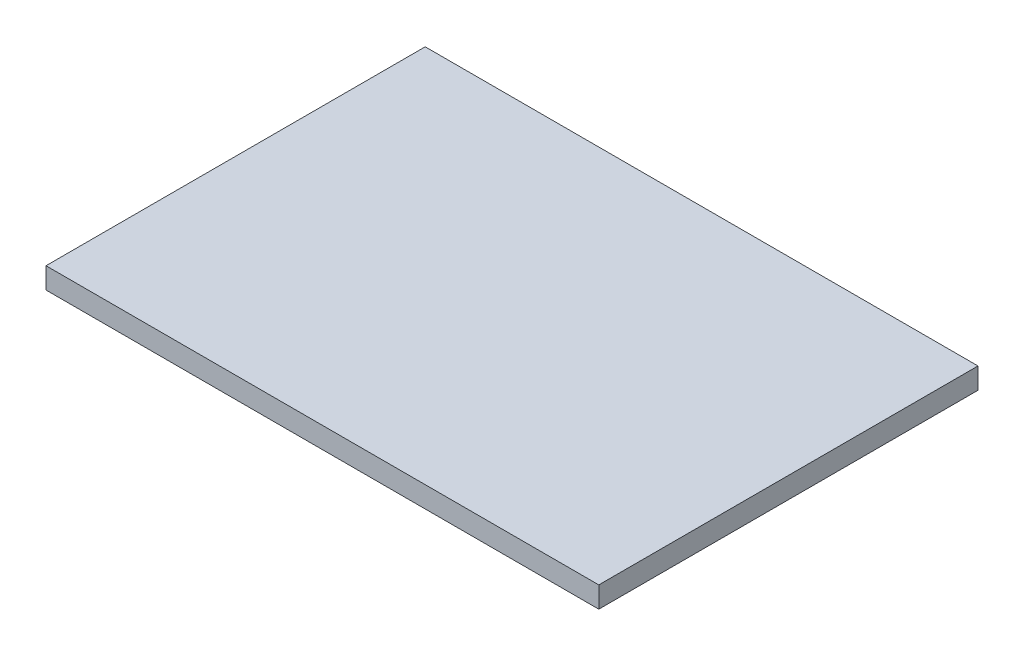
SolidWorks part; units mm, degrees
material "Acrylic (Medium-high impact)"
ref_plane "Front Plane" through (0, 0, 0) normal (0, 0, 1) x (1, 0, 0)
ref_plane "Top Plane" through (0, 0, 0) normal (0, 1, 0) x (1, 0, 0)
ref_plane "Right Plane" through (0, 0, 0) normal (1, 0, 0) x (0, 0, -1)
sketch "Sketch2" plane through (0, 0, 0) normal (0, 1, 0) x (1, 0, 0)
  line L1 (-181.8091, 28.5522) -> (-50.6091, 28.5522)
  line L2 (-181.8091, 28.5522) -> (-181.8091, -61.4478)
  line L3 (-181.8091, -61.4478) -> (-50.6091, -61.4478)
  line L4 (-50.6091, 28.5522) -> (-50.6091, -61.4478)
  dimension "D1" = 90
  dimension "D2" = 131.2
extrude "Boss-Extrude1" add sketch "Sketch2" along normal blind 5
sketch "Sketch5" plane through (0, 5, 0) normal (0, 1, 0) x (1, 0, 0)
  line L1 (-181.8091, -61.4478) -> (-50.6091, -61.4478) construction
  line L2 (-50.6091, -61.4478) -> (-50.6091, 28.5522) construction
sketch_block_instance "Block4-13"
sketch_block "Block4" parameters "D1"=11.2, "D2"=11.2, "D3"=11.2, "D4"=18.4, "D5"=19.2, "D6"=18.4, "D7"=10.4, "D8"=18.4, "D9"=10.4, "D10"=10.4, "D11"=18.4, "D12"=19.2, "D13"=90, "D14"=52, "D15"=131.2
